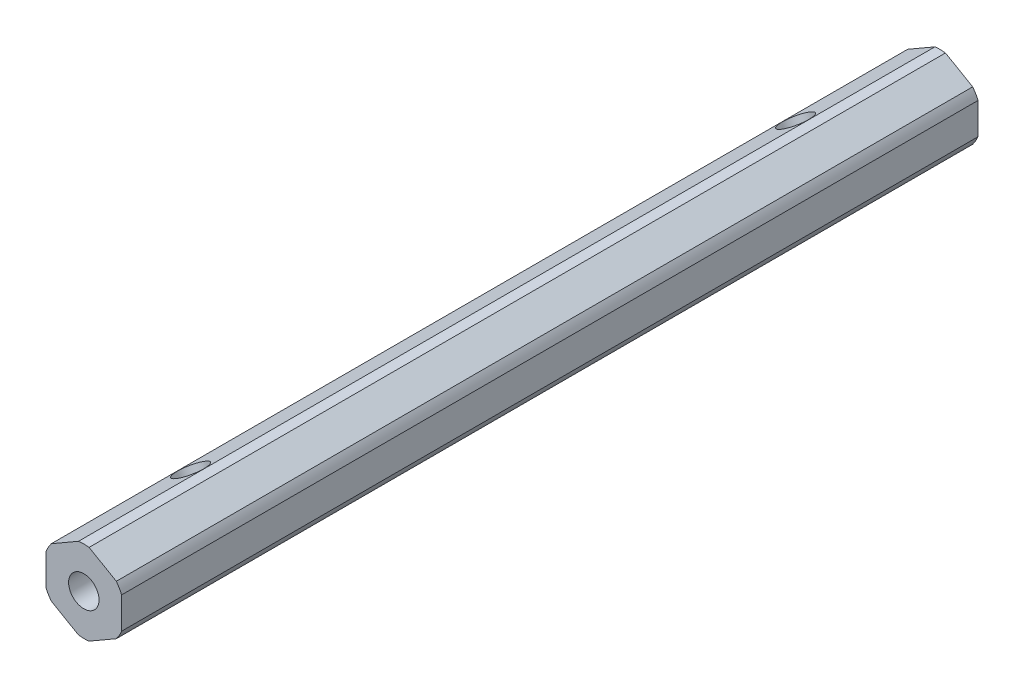
SolidWorks part; units mm, degrees
material "7075-T6 (SN)"
ref_plane "Front" through (0, 0, 0) normal (0, 0, 1) x (1, 0, 0)
ref_plane "Top" through (0, 0, 0) normal (0, 1, 0) x (1, 0, 0)
ref_plane "Right" through (0, 0, 0) normal (1, 0, 0) x (0, 0, -1)
sketch "Sketch1" plane through (0, 0, 0) normal (0, 0, 1) x (1, 0, 0)
  line L1 (0, 7.3323) -> (-6.35, 3.6662)
  line L2 (-6.35, 3.6662) -> (-6.35, -3.6662)
  line L3 (-6.35, -3.6662) -> (0, -7.3323)
  line L4 (0, -7.3323) -> (6.35, -3.6662)
  line L5 (6.35, -3.6662) -> (6.35, 3.6662)
  line L6 (6.35, 3.6662) -> (0, 7.3323)
  circle A0 centre (0, 0) radius 6.35 construction
  dimension "D1" = 12.7
extrude "Shaft Boss" add sketch "Sketch1" along normal mid plane 914.4
sketch "Sketch2" plane through (0, 0, -457.2) normal (0, 0, -1) x (-1, 0, 0)
  circle A0 centre (0, 0) radius 6.877
  circle A1 centre (0, 0) radius 9.417
  dimension "D1" = 13.7541
  dimension "D2" = 2.54
extrude "Cut For Thunder Hex Round" cut sketch "Sketch2" against normal blind 914.4
sketch "Sketch3" plane through (0, 0, -457.2) normal (0, 0, -1) x (-1, 0, 0)
  circle A0 centre (0, 0) radius 2.5527
  dimension "D1" = 5.1054
extrude "Center Hole Cut" cut sketch "Sketch3" against normal blind 914.4
ref_plane "Plane1" through (0, 0, 71.9105) normal (0, 0, -1) x (-1, 0, 0)
other "SurfaceCut1"
ref_plane "Plane2" through (0, 0, -71.9105) normal (0, 0, 1) x (1, 0, 0)
other "SurfaceCut2"
hole_wizard "#10 Clearance Hole1" positions "Sketch4" profile "Sketch5" hole size "#10" standard "ANSI Inch" end condition through all
sketch "Sketch4" plane through (3.175, -5.4993, 0) normal (0.5, -0.866, 0) x (-0.866, -0.5, 0)
  line L0 (0, 50.8) -> (0, 0) construction
  line L1 (0, 0) -> (0, -50.8) construction
  point P0 (0, 50.8)
  point P5 (0, -50.8)
  dimension "D1" = 50.8
sketch "Sketch5" plane through (3.175, -5.4993, -50.8) normal (0, 0, 1) x (0.866, 0.5, 0)
  line L0 (0, 0) -> (0, 15.4807)
  line L1 (0, 15.4807) -> (2.5527, 15.4807)
  line L2 (2.5527, 15.4807) -> (2.5527, 0)
  line L5 (2.5527, 0) -> (0, 0)
  line L11 (0, -6.35) -> (0, 107.95) construction
  dimension "Thru Hole Dia." = 5.1054
  dimension "Thru Hole Depth" = 15.4807
equation "\"HS\"= .5"
equation "\"L\"= 36"
equation "\"D1@Sketch1\"=\"HS\""
equation "\"D1@Shaft Boss\" = \"L\""
equation "\"THOD\"= .5415"
equation "\"Fillet1\"      = \"suppressed\""
equation "\"Shaft Boss\"= \"unsuppressed\""
equation "\"D1@Sketch2\"=\"THOD\""
equation "\"D1@Cut For Thunder Hex Round\" = \"L\""
equation "\"Cut For Thunder Hex Round\"    = \"unsuppressed\""
equation "\"THID\"= .201"
equation "\"D1@Sketch3\"=\"THID\""
equation "\"D1@Center Hole Cut\" = \"L\""
equation "\"Center Hole Cut\"     = \"unsuppressed\""
